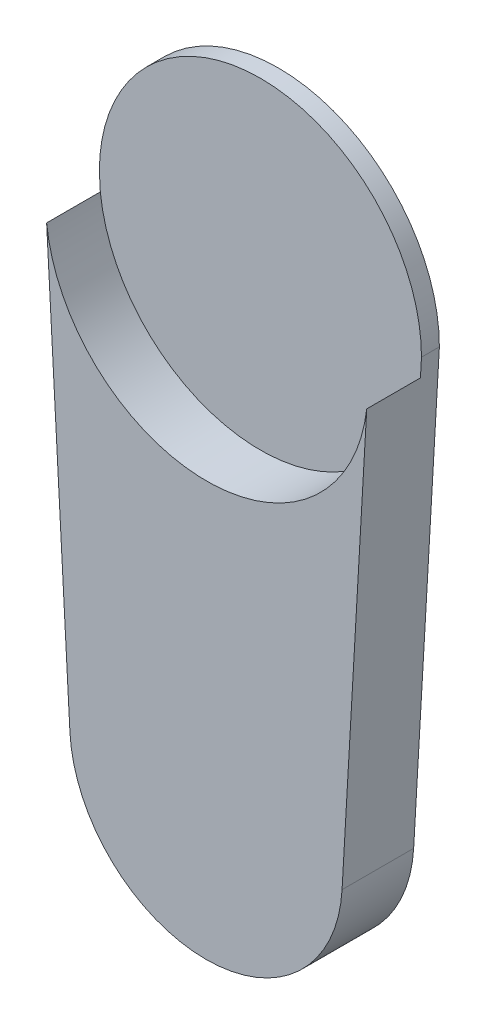
SolidWorks part; units mm, degrees
ref_plane "Front Plane" through (0, 0, 0) normal (0, 0, 1) x (1, 0, 0)
ref_plane "Top Plane" through (0, 0, 0) normal (0, 1, 0) x (1, 0, 0)
ref_plane "Right Plane" through (0, 0, 0) normal (1, 0, 0) x (0, 0, -1)
sketch "Sketch2" plane through (0, 0, 0) normal (0, 0, 1) x (1, 0, 0)
  line L0 (-90, 0) -> (-76.4484, -249.6324)
  line L1 (90, 0) -> (75.6281, -249.8772)
  circle A0 centre (0, 0) radius 90
  arc A1 (-76.4484, -249.6324) -> (75.6281, -249.8772) centre (-0.4033, -245.5042) ccw
extrude "Boss-Extrude3" add sketch "Sketch2" along normal blind 10 contours L1 A0 L0 | L0 A1 L1 A0
sketch "Sketch3" plane through (0, 0, 10) normal (0, 0, 1) x (1, 0, 0)
  line L0 (-90, 0) -> (-76.4484, -249.6324)
  line L1 (75.6281, -249.8772) -> (90, 0)
  circle A0 centre (0, 0) radius 90
  arc A1 (-76.4484, -249.6324) -> (75.6281, -249.8772) centre (-0.4033, -245.5042) ccw
  line M2 (75.6281, -249.8772) -> (90, 0)
  arc M5 (-76.4484, -249.6324) -> (75.6281, -249.8772) centre (-0.4033, -245.5042) ccw
extrude "Boss-Extrude4" add sketch "Sketch3" along normal blind 30 contours A0 L0 M5 M2
